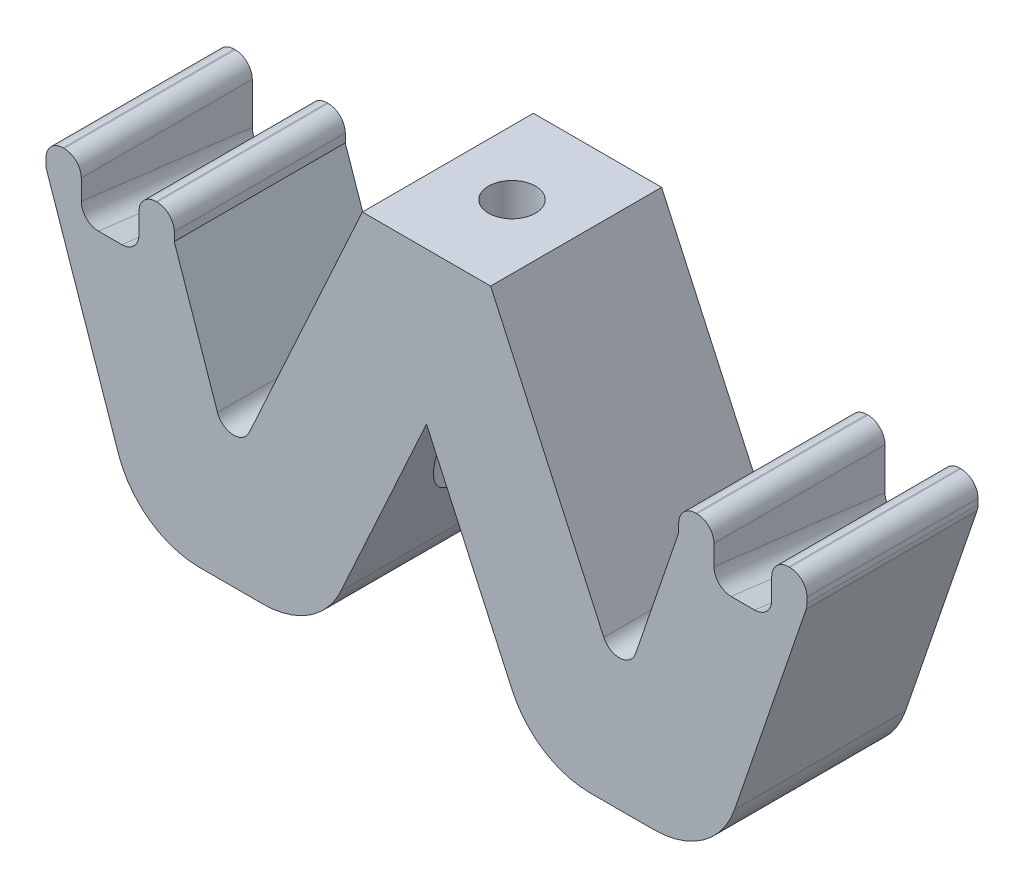
SolidWorks part; units mm, degrees
ref_plane "Front" through (0, 0, 0) normal (0, 0, 1) x (1, 0, 0)
ref_plane "Top" through (0, 0, 0) normal (0, 1, 0) x (1, 0, 0)
ref_plane "Right" through (0, 0, 0) normal (1, 0, 0) x (0, 0, -1)
sketch "Sketch1" plane through (0, 0, 0) normal (0, 0, 1) x (1, 0, 0)
  line L0 (-70, 0) -> (70, 0)
  line L1 (-70, 0) -> (-70, 12)
  line L2 (-57.5, 24.5) -> (-25, 24.5)
  line L3 (-25, 24.5) -> (-25, 39.5)
  line L6 (0, -50) -> (0, 50) construction
  line L8 (25, 24.5) -> (25, 39.5)
  line L9 (57.5, 24.5) -> (25, 24.5)
  line L10 (70, 0) -> (70, 12)
  line L11 (-25, 39.5) -> (-44.5, 96.5)
  line L12 (-44.5, 96.5) -> (-29.5, 96.5)
  line L13 (-29.5, 96.5) -> (0, 10.2692)
  line L14 (29.5, 96.5) -> (0, 10.2692)
  line L15 (44.5, 96.5) -> (29.5, 96.5)
  line L16 (25, 39.5) -> (44.5, 96.5)
  circle A0 centre (-57.5, 12) radius 4
  arc A4 (-70, 12) -> (-57.5, 24.5) centre (-57.5, 12) cw
  arc A5 (70, 12) -> (57.5, 24.5) centre (57.5, 12) ccw
  circle A6 centre (57.5, 12) radius 4
  point P8 (0, 0)
  point P27 (-37, 96.5)
  point P28 (37, 96.5)
  dimension "D2" = 8
  dimension "D1" = 140
  dimension "D3" = 12
  dimension "D4" = 115
  dimension "D5" = 50
  dimension "D6" = 15
  dimension "D7" = 96.5
  dimension "D8" = 15
  dimension "D9" = 74
extrude "Boss-Extrude1" add sketch "Sketch1" along normal blind 20
fillet "Fillet1" radius 10 5 edges at (0, 10.2692, 10) (25, 39.5, 10) (25, 24.5, 10) (-25, 39.5, 10) (-25, 24.5, 10)
sketch "Sketch9" plane through (0, 0, 0) normal (1, 0, 0) x (0, 0, -1)
  line L0 (-20, 96.5) -> (0, 94)
  line L1 (0, 96.5) -> (0, 41.0737) construction
  dimension "D1" = 2.5
sketch "Sketch2" plane through (0, 0, 20) normal (0, 0, 1) x (1, 0, 0)
  line L2 (44.5, 96.5) -> (29.5, 96.5) construction
  line L3 (33.625, 93.125) -> (40.375, 93.125)
  line L4 (33.625, 93.125) -> (33.625, 99.875)
  line L5 (33.625, 99.875) -> (40.375, 99.875)
  line L6 (40.375, 93.125) -> (40.375, 99.875)
  line L7 (33.625, 93.125) -> (40.375, 99.875) construction
  line L8 (33.625, 99.875) -> (40.375, 93.125) construction
  line L9 (-29.5, 96.5) -> (-44.5, 96.5) construction
  line L10 (-40.375, 93.125) -> (-33.625, 93.125)
  line L11 (-40.375, 93.125) -> (-40.375, 99.875)
  line L12 (-40.375, 99.875) -> (-33.625, 99.875)
  line L13 (-33.625, 93.125) -> (-33.625, 99.875)
  line L14 (-40.375, 93.125) -> (-33.625, 99.875) construction
  line L15 (-40.375, 99.875) -> (-33.625, 93.125) construction
  point P0 (-37, 96.5)
  point P4 (37, 96.5)
  point P7 (37, 96.5)
  dimension "D2" = 6.75
extrude "Cut-Extrude1" cut sketch "Sketch2" along direction (0, -0.124, -0.9923) on the side against the normal through all
sketch "Sketch3" plane through (0, 96.5, 0) normal (0, 1, 0) x (1, 0, 0)
  line L0 (44.5, 0) -> (40.375, 0) construction
  line L2 (40.375, -20) -> (44.5, -20) construction
  line L3 (44.5, -20) -> (44.5, 0) construction
  line L4 (29.5, -20) -> (33.625, -20) construction
  line L6 (33.625, 0) -> (29.5, 0) construction
  line L7 (29.5, 0) -> (29.5, -20) construction
  line L8 (-29.5, 0) -> (-33.625, 0) construction
  line L10 (-33.625, -20) -> (-29.5, -20) construction
  line L11 (-29.5, -20) -> (-29.5, 0) construction
  line L12 (-44.5, -20) -> (-40.375, -20) construction
  line L14 (-40.375, 0) -> (-44.5, 0) construction
  line L15 (-44.5, 0) -> (-44.5, -20) construction
  line L16 (44.5, 0) -> (40.375, 0)
  line L17 (40.375, 0) -> (40.375, -20)
  line L18 (40.375, -20) -> (44.5, -20)
  line L19 (44.5, -20) -> (44.5, 0)
  line L20 (29.5, -20) -> (33.625, -20)
  line L21 (33.625, -20) -> (33.625, 0)
  line L22 (33.625, 0) -> (29.5, 0)
  line L23 (29.5, 0) -> (29.5, -20)
  line L24 (-29.5, 0) -> (-33.625, 0)
  line L25 (-33.625, 0) -> (-33.625, -20)
  line L26 (-33.625, -20) -> (-29.5, -20)
  line L27 (-29.5, -20) -> (-29.5, 0)
  line L28 (-44.5, -20) -> (-40.375, -20)
  line L29 (-40.375, -20) -> (-40.375, 0)
  line L30 (-40.375, 0) -> (-44.5, 0)
  line L31 (-44.5, 0) -> (-44.5, -20)
extrude "Boss-Extrude2" add sketch "Sketch3" along normal blind 3
fillet "Fillet2" radius 2 13 edges at (-44.5, 99.5, 10) (-40.375, 99.5, 10) (-33.625, 99.5, 10) (-29.5, 99.5, 10) (29.5, 99.5, 10) (33.625, 99.5, 10) (40.375, 99.5, 10) (44.5, 99.5, 10) (44.5, 96.5, 10) (33.625, 91.875, 10) (40.375, 91.875, 10) (-33.625, 91.875, 10) (-40.375, 91.875, 10)
sketch "Sketch4" plane through (0, 0, 20) normal (0, 0, 1) x (1, 0, 0)
  line L0 (-22.8209, 76.9766) -> (-7.5, 110.5)
  line L1 (-38.375, 93.125) -> (-35.625, 93.125) construction
  line L2 (-38.5933, 79.2342) -> (-25.1649, 83.8281) construction
  line L3 (-44.5, 96.5) -> (-25.5384, 41.0737) construction
  line L10 (-9.4616, 37.9263) -> (-29.5, 96.5) construction
  line L11 (-7.5, 110.5) -> (7.5, 110.5)
  line L12 (7.5, 110.5) -> (22.8209, 76.9766)
  line L13 (29.5, 96.5) -> (9.4616, 37.9263) construction
  line L14 (22.8209, 76.9766) -> (16.1407, 57.4498)
  line L15 (16.1407, 57.4498) -> (0, 92.7669)
  line L16 (0, 92.7669) -> (-16.1407, 57.4498)
  line L17 (-16.1407, 57.4498) -> (-22.8209, 76.9766)
  line L18 (-16.6165, 90.5524) -> (-3.7082, 84.6531) construction
  point P13 (0, 110.5)
  point P16 (19.4808, 67.2132)
  point P17 (19.4808, 67.2132)
  dimension "D1" = 17.375
  dimension "D2" = 15
extrude "Boss-Extrude3" add sketch "Sketch4" against normal up to surface (20 mm away) up to face at (0.9871, 71.3824, 0)
sketch "Sketch6" plane through (0, 0, 20) normal (0, 0, 1) x (1, 0, 0)
  line L1 (70, 0) -> (-70, 0)
  line L2 (70, 0) -> (70, 64.9766)
  line L3 (70, 64.9766) -> (-70, 64.9766)
  line L4 (-70, 0) -> (-70, 64.9766)
  dimension "D1" = 12
extrude "Cut-Extrude3" cut sketch "Sketch6" against normal through all
sketch "Sketch7" plane through (0, 64.9766, 0) normal (0, -1, 0) x (1, 0, 0)
  line L0 (0, 0) -> (0, 20) construction
  circle A0 centre (0, 10) radius 6.5
  dimension "D1" = 13
extrude "Cut-Extrude4" cut sketch "Sketch7" against normal offset from surface (35.5234 mm away) 10 up to face at (0, 110.5, 10)
fillet "Fillet5" radius 2 2 edges at (22.8209, 76.9766, 10) (-22.8209, 76.9766, 10)
fillet "Fillet6" radius 10 4 edges at (33.7157, 64.9766, 10) (12.7008, 64.9766, 10) (-12.7008, 64.9766, 10) (-33.7157, 64.9766, 10)
sketch "Sketch8" plane through (0, 100.5, 0) normal (0, -1, 0) x (1, 0, 0)
  circle A0 centre (0, 10) radius 2.75
  dimension "D1" = 5.5
extrude "Cut-Extrude5" cut sketch "Sketch8" against normal through all
sketch "Sketch5" plane through (0, 110.5, 0) normal (0, 1, 0) x (1, 0, 0)
  line L0 (7.5, 0) -> (7.5, -20) construction
  circle A0 centre (0, -10) radius 3
  point P5 (7.5, -10)
  dimension "D1" = 6
